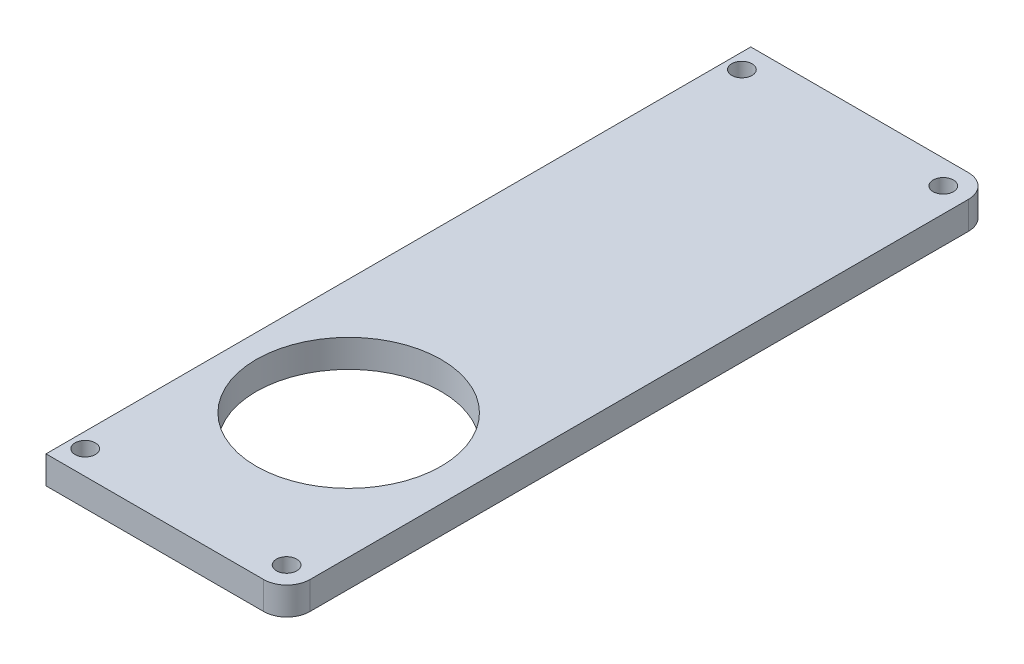
SolidWorks part; units mm, degrees
material "Acrylic (Medium-high impact)"
ref_plane "Front Plane" through (0, 0, 0) normal (0, 0, 1) x (1, 0, 0)
ref_plane "Top Plane" through (0, 0, 0) normal (0, 1, 0) x (1, 0, 0)
ref_plane "Right Plane" through (0, 0, 0) normal (1, 0, 0) x (0, 0, -1)
sketch "Sketch1" plane through (0, 0, 0) normal (0, 1, 0) x (1, 0, 0)
  line L1 (-13.0188, -38.1) -> (10.5187, -38.1)
  line L2 (-13.0188, -38.1) -> (-13.0188, 38.1)
  line L3 (-13.0188, 38.1) -> (10.5187, 38.1)
  line L4 (13.0188, -35.6) -> (13.0188, 35.6)
  line L5 (-13.0188, -38.1) -> (13.0188, 38.1) construction
  line L6 (-13.0188, 38.1) -> (13.0188, -38.1) construction
  arc A0 (10.5187, -38.1) -> (13.0188, -35.6) centre (10.5188, -35.6) ccw
  arc A1 (13.0188, 35.6) -> (10.5187, 38.1) centre (10.5188, 35.6) ccw
  circle A2 centre (-11.3813, 35.5) radius 1.1
  circle A3 centre (10.3938, 35.5) radius 1.1
  circle A4 centre (-11.3813, -35.5) radius 1.1
  circle A5 centre (10.3938, -35.5) radius 1.1
  circle A6 centre (-0.4937, -17.9) radius 10
  point P0 (0, 0)
  dimension "D3" = 2.5
  dimension "D5" = 2.2
  dimension "D7" = 2.2
  dimension "D8" = 2.6
  dimension "D11" = 2.2
  dimension "D12" = 2.2
  dimension "D17" = 20
  dimension "D1" = 26.0375
  dimension "D2" = 76.2
  dimension "D4" = 1.6375
  dimension "D6" = 2.6
  dimension "D9" = 2.625
  dimension "D10" = 1.6375
  dimension "D13" = 2.625
  dimension "D14" = 2.6
  dimension "D15" = 2.6
  dimension "D16" = 13.5125
  dimension "D18" = 20.2
extrude "Boss-Extrude1" add sketch "Sketch1" along normal blind 3
